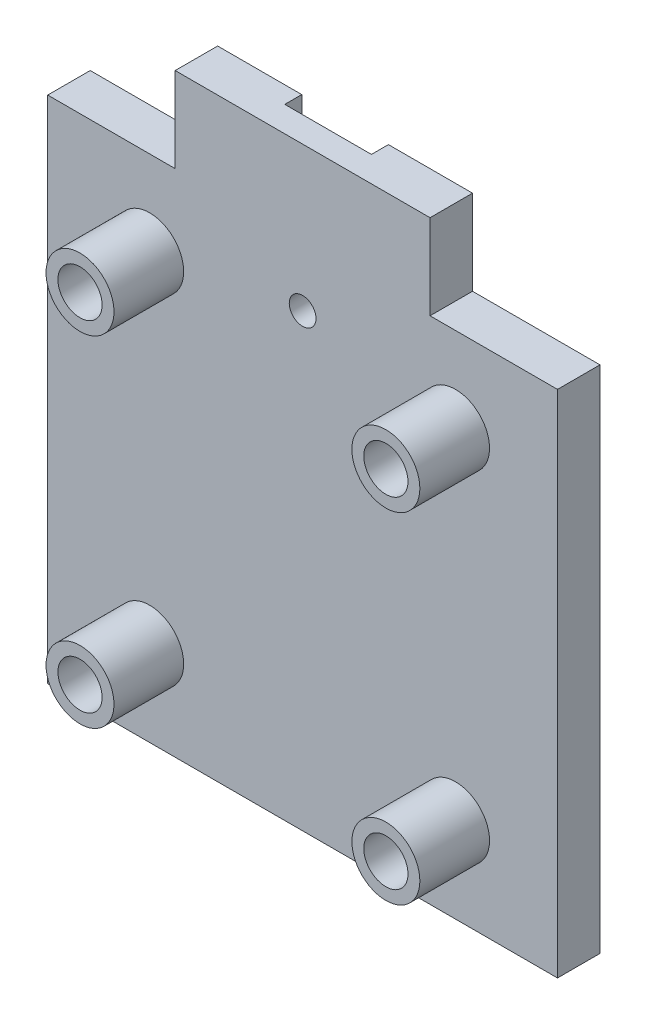
SolidWorks part; units mm, degrees
ref_plane "Front Plane" through (0, 0, 0) normal (0, 0, 1) x (1, 0, 0)
ref_plane "Top Plane" through (0, 0, 0) normal (0, 1, 0) x (1, 0, 0)
ref_plane "Right Plane" through (0, 0, 0) normal (1, 0, 0) x (0, 0, -1)
sketch "Sketch1" plane through (0, 0, 0) normal (0, 0, 1) x (1, 0, 0)
  line L1 (-19.05, -38.1) -> (19.05, -38.1)
  line L2 (-19.05, -38.1) -> (-19.05, 38.1)
  line L3 (-19.05, 38.1) -> (19.05, 38.1)
  line L4 (19.05, -38.1) -> (19.05, 38.1)
  line L5 (-19.05, -38.1) -> (19.05, 38.1) construction
  line L6 (-19.05, 38.1) -> (19.05, -38.1) construction
  point P0 (0, 0)
  dimension "D1" = 38.1
  dimension "D2" = 76.2
extrude "Boss-Extrude1" add sketch "Sketch1" along normal blind 6.35
sketch "Sketch8" plane through (0, 0, 6.35) normal (0, 0, 1) x (1, 0, 0)
  line L0 (19.05, 38.1) -> (-19.05, 38.1) construction
  line L1 (-19.05, 38.1) -> (-38.1, 38.1)
  line L2 (-19.05, 38.1) -> (-19.05, -38.1)
  line L3 (-19.05, -38.1) -> (-38.1, -38.1)
  line L4 (-38.1, 38.1) -> (-38.1, -38.1)
  line L5 (-19.05, 38.1) -> (-19.05, -38.1) construction
  line L6 (-19.05, -38.1) -> (19.05, -38.1) construction
  line L7 (0, 38.1) -> (0, -38.1) construction
  line L8 (19.05, -38.1) -> (38.1, -38.1)
  line L9 (38.1, 38.1) -> (38.1, -38.1)
  line L10 (19.05, 38.1) -> (38.1, 38.1)
  line L11 (19.05, 38.1) -> (19.05, -38.1)
  dimension "D1" = 38.1
extrude "Boss-Extrude5" add sketch "Sketch8" against normal up to surface (6.35 mm away) up to face at (0, 0, 0)
sketch "Sketch5" plane through (0, 0, 6.35) normal (0, 0, 1) x (1, 0, 0)
  line L0 (38.1, 38.1) -> (-38.1, 38.1) construction
  line L1 (0, 38.1) -> (0, -38.1) construction
  line L2 (38.1, 38.1) -> (-38.1, 38.1) construction
  line L3 (-38.1, -38.1) -> (38.1, -38.1) construction
  circle A0 centre (22.86, 25.4) radius 5.08
  circle A1 centre (-22.86, 25.4) radius 5.08
  dimension "D1" = 10.16
  dimension "D2" = 12.7
  dimension "D3" = 22.86
extrude "Boss-Extrude2" add sketch "Sketch5" along normal blind 10.414
sketch "Sketch6" plane through (0, 0, 16.764) normal (0, 0, 1) x (1, 0, 0)
  line L0 (0, 38.1) -> (0, -38.1) construction
  line L1 (38.1, 38.1) -> (-38.1, 38.1) construction
  line L2 (-38.1, -38.1) -> (38.1, -38.1) construction
  circle A0 centre (22.86, 25.4) radius 3.302
  circle A1 centre (-22.86, 25.4) radius 3.302
  dimension "D1" = 6.604
extrude "Cut-Extrude3" cut sketch "Sketch6" against normal through all
mirror "Mirror1" about plane through (0, 0, 0) normal (0, 1, 0) of "Cut-Extrude3", "Boss-Extrude2"
sketch "Sketch7" plane through (0, 0, 6.35) normal (0, 0, 1) x (1, 0, 0)
  line L0 (0, 50.8) -> (0, -38.1) construction
  line L1 (-19.05, 38.1) -> (19.05, 38.1)
  line L2 (-19.05, 38.1) -> (-19.05, 50.8)
  line L3 (-19.05, 50.8) -> (19.05, 50.8)
  line L4 (19.05, 38.1) -> (19.05, 50.8)
  line L6 (-19.05, 44.45) -> (19.05, 44.45) construction
  line L7 (-12.7, 50.8) -> (-12.7, 38.1) construction
  line L8 (-38.1, -38.1) -> (38.1, -38.1) construction
  line L9 (38.1, 38.1) -> (-38.1, 38.1) construction
  dimension "D1" = 12.7
  dimension "D2" = 6.35
  dimension "D5" = 38.1
extrude "Boss-Extrude4" add sketch "Sketch7" against normal up to surface (6.35 mm away) up to face at (26.162, -25.4, 0)
sketch "Sketch9" plane through (0, 0, 0) normal (0, 0, -1) x (-1, 0, 0)
  line L0 (0, 50.8) -> (0, -38.1) construction
  line L1 (-19.05, 50.8) -> (19.05, 50.8) construction
  line L2 (38.1, -38.1) -> (-38.1, -38.1) construction
  line L3 (-19.05, 44.45) -> (19.05, 44.45) construction
  line L4 (-19.05, 38.1) -> (-19.05, 50.8) construction
  line L5 (19.05, 50.8) -> (19.05, 38.1) construction
  circle A0 centre (0, 29.21) radius 2
  dimension "D1" = 4
  dimension "D2" = 15.24
extrude "Cut-Extrude4" cut sketch "Sketch9" against normal through all
sketch "Sketch10" plane through (0, 0, 0) normal (0, 0, 1) x (1, 0, 0)
  line L0 (0, 50.8) -> (0, -38.1) construction
  line L1 (19.05, 50.8) -> (-19.05, 50.8) construction
  line L2 (-38.1, -38.1) -> (38.1, -38.1) construction
  line L4 (-6.477, 24.67) -> (6.477, 24.67)
  line L5 (-6.477, 24.67) -> (-6.477, 50.8)
  line L6 (-6.477, 50.8) -> (6.477, 50.8)
  line L7 (6.477, 24.67) -> (6.477, 50.8)
  line L8 (-6.477, 24.67) -> (6.477, 50.8) construction
  line L9 (-6.477, 50.8) -> (6.477, 24.67) construction
  circle A0 centre (0, 29.21) radius 2 construction
  point P12 (0, 31.21)
  point P13 (0, 0)
  point P16 (0, 37.735)
  point P18 (0, 27.21)
  dimension "D2" = 12.954
  dimension "D3" = 2.54
extrude "Cut-Extrude5" cut sketch "Sketch10" along normal blind 2.54
